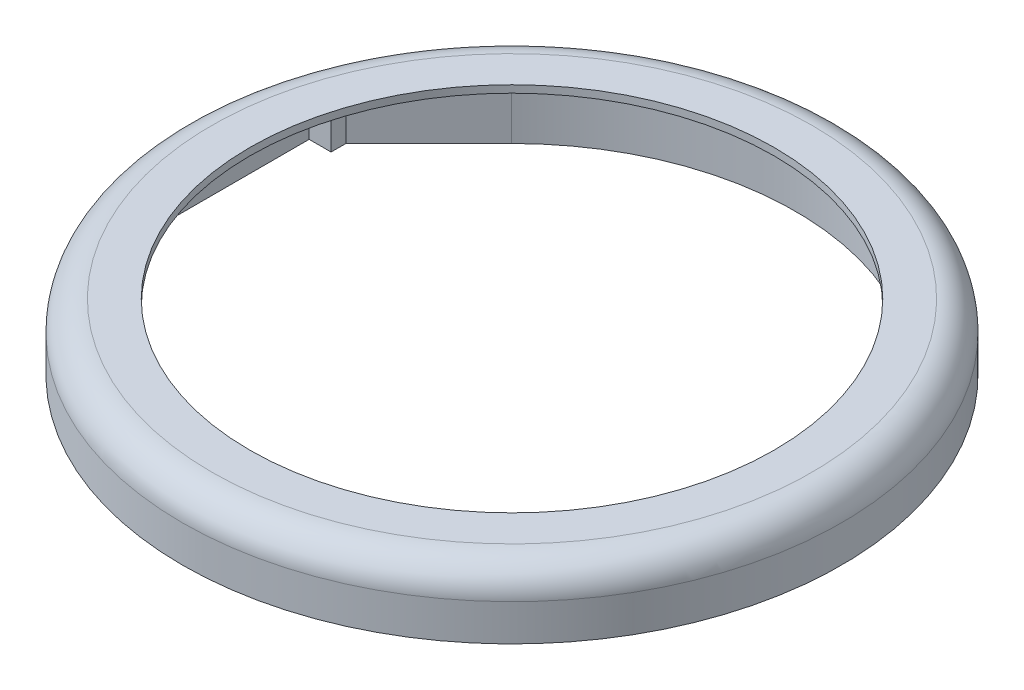
SolidWorks part; units mm, degrees
ref_plane "Front Plane" through (0, 0, 0) normal (0, 0, 1) x (1, 0, 0)
ref_plane "Top Plane" through (0, 0, 0) normal (0, 1, 0) x (1, 0, 0)
ref_plane "Right Plane" through (0, 0, 0) normal (1, 0, 0) x (0, 0, -1)
sketch "Sketch1" plane through (0, 0, 0) normal (0, 1, 0) x (1, 0, 0)
  circle A0 centre (0, 0) radius 22.5
  dimension "D1" = 45
extrude "Boss-Extrude1" add sketch "Sketch1" along normal blind 4.5
sketch "Sketch2" plane through (0, 4.5, 0) normal (0, 1, 0) x (1, 0, 0)
  circle A0 centre (0, 0) radius 17.9
  dimension "D1" = 35.8
extrude "Cut-Extrude1" cut sketch "Sketch2" against normal through all
sketch "Sketch3" plane through (0, 0, 0) normal (0, -1, 0) x (1, 0, 0)
  line L0 (-13.7007, -13.6644) -> (-19.35, -8)
  line L1 (-19.35, -8) -> (-19.35, 8)
  line L2 (-19.35, 8) -> (-13.7007, 13.6644)
  arc A0 (-13.7007, -13.6644) -> (-13.7007, 13.6644) centre (0, 0) ccw
  arc A1 (-19.35, 0) -> (-13.7007, -13.6644) centre (0, 0) ccw construction
  arc A2 (-13.7007, 13.6644) -> (-19.35, 0) centre (0, 0) ccw construction
  point P1 (-18.9842, -8.8331)
  point P5 (26.1567, 9.8193)
  point P8 (25.4573, -7.9449)
  point P9 (26.7721, -13.484)
  point P10 (20.5057, -6.0986)
  point P11 (19.35, 8)
  dimension "D1" = 38.7
  dimension "D2" = 16
extrude "Cut-Extrude2" cut sketch "Sketch3" against normal offset from surface (4 mm away) 0.5 up to face at (0, 4.5, 17.9)
sketch "Sketch4" plane through (0, 0, 0) normal (0, -1, 0) x (1, 0, 0)
  line L0 (-20.85, 7) -> (-19.35, 7)
  line L2 (-19.35, 7) -> (-19.35, -7)
  line L3 (-19.35, -7) -> (-20.85, -7)
  line L4 (-20.85, 7) -> (-20.85, -7)
  line L5 (-19.35, 8) -> (-19.35, -8) construction
  point P2 (-29.4578, 9.1199)
  point P4 (19.35, 13.8412)
  point P9 (-19.35, 0)
  point P10 (-17.85, 14.0715)
  point P11 (-19.35, 13.7637)
  point P13 (-30.7726, -5.7629)
  point P14 (-19.35, 0)
  dimension "D1" = 14
  dimension "D2" = 1.5
extrude "Cut-Extrude3" cut sketch "Sketch4" against normal offset from surface (3.2 mm away) 0.8 up to face at (-8.2627, 4, 0)
fillet "Fillet2" radius 2 1 edges at (0, 4.5, 22.5)
sketch "Sketch5" plane through (0, 0, 0) normal (0, -1, 0) x (1, 0, 0)
  line L0 (-12.8151, 17.1963) -> (-12.0651, 15.8973)
  line L1 (-12.8151, 17.1963) -> (-8.4849, 19.6963)
  line L2 (-12.0651, 15.8973) -> (-7.7349, 18.3973)
  line L3 (-8.4849, 19.6963) -> (-7.7349, 18.3973)
  line L4 (19.8, 2.5) -> (21.3, 2.5)
  line L5 (19.8, 2.5) -> (19.8, -2.5)
  line L6 (21.3, 2.5) -> (21.3, -2.5)
  line L7 (19.8, -2.5) -> (21.3, -2.5)
  line L8 (-12.8151, -17.1963) -> (-8.4849, -19.6963)
  line L9 (-12.8151, -17.1963) -> (-12.0651, -15.8973)
  line L10 (-8.4849, -19.6963) -> (-7.7349, -18.3973)
  line L11 (-12.0651, -15.8973) -> (-7.7349, -18.3973)
  line L12 (-9.9, 17.1473) -> (0, 0) construction
  line L13 (0, 0) -> (19.8, 0) construction
  line L14 (0, 0) -> (-9.9, -17.1473) construction
  line L15 (22.5, 0) -> (21.3, 0) construction
  circle A0 centre (0, 0) radius 22.5 construction
  point P18 (1.147, 1.7904)
  point P19 (0, 0)
  point P21 (0, 0)
  dimension "D1" = 120
  dimension "D2" = 120
  dimension "D3" = 120
  dimension "D4" = 1.5
  dimension "D5" = 5
  dimension "D6" = 1.2
extrude "Cut-Extrude4" cut sketch "Sketch5" against normal blind 4
sketch "Sketch6" plane through (-9.9, 0, 17.1473) normal (-0.5, 0, 0.866) x (0.866, 0, 0.5)
  line L4 (-2.5, 0) -> (2.5, 0)
  line L5 (2.5, 0) -> (2.5, 4)
  line L6 (2.5, 4) -> (-2.5, 4)
  line L7 (-2.5, 4) -> (-2.5, 0)
  line L8 (-2.5, 0) -> (2.5, 0) construction
  line L9 (2.5, 0) -> (2.5, 4) construction
  line L10 (2.5, 4) -> (-2.5, 4) construction
  line L11 (-2.5, 4) -> (-2.5, 0) construction
  circle A0 centre (2.5, 2.5) radius 1.5
  circle A1 centre (-2.5, 2.5) radius 1.5
  dimension "D2" = 3
  dimension "D1" = 0
extrude "Cut-Extrude5" cut sketch "Sketch6" along normal up to surface (1.5 mm away) up to face at (-10.65, 2, 18.4463)
sketch "Sketch7" plane through (-9.9, 0, -17.1473) normal (-0.5, 0, -0.866) x (-0.866, 0, 0.5)
  line L4 (-2.5, 0) -> (2.5, 0)
  line L5 (2.5, 0) -> (2.5, 4)
  line L6 (2.5, 4) -> (-2.5, 4)
  line L7 (-2.5, 4) -> (-2.5, 0)
  line L8 (-2.5, 0) -> (2.5, 0) construction
  line L9 (2.5, 0) -> (2.5, 4) construction
  line L10 (2.5, 4) -> (-2.5, 4) construction
  line L11 (-2.5, 4) -> (-2.5, 0) construction
  circle A0 centre (-2.5, 2.5) radius 1.5
  circle A1 centre (2.5, 2.5) radius 1.5
  dimension "D2" = 3
  dimension "D1" = 0
extrude "Cut-Extrude6" cut sketch "Sketch7" along normal up to surface (1.5 mm away) up to face at (-10.65, 2, -18.4463)
sketch "Sketch8" plane through (19.8, 0, 0) normal (1, 0, 0) x (0, 0, -1)
  line L4 (-2.5, 0) -> (2.5, 0)
  line L5 (2.5, 0) -> (2.5, 4)
  line L6 (2.5, 4) -> (-2.5, 4)
  line L7 (-2.5, 4) -> (-2.5, 0)
  line L8 (-2.5, 0) -> (2.5, 0) construction
  line L9 (2.5, 0) -> (2.5, 4) construction
  line L10 (2.5, 4) -> (-2.5, 4) construction
  line L11 (-2.5, 4) -> (-2.5, 0) construction
  circle A0 centre (2.5, 2.5) radius 1.5
  circle A1 centre (-2.5, 2.5) radius 1.5
  dimension "D2" = 3
  dimension "D1" = 0
extrude "Cut-Extrude7" cut sketch "Sketch8" along normal up to surface (1.5 mm away) up to face at (21.3, 2, 0)
